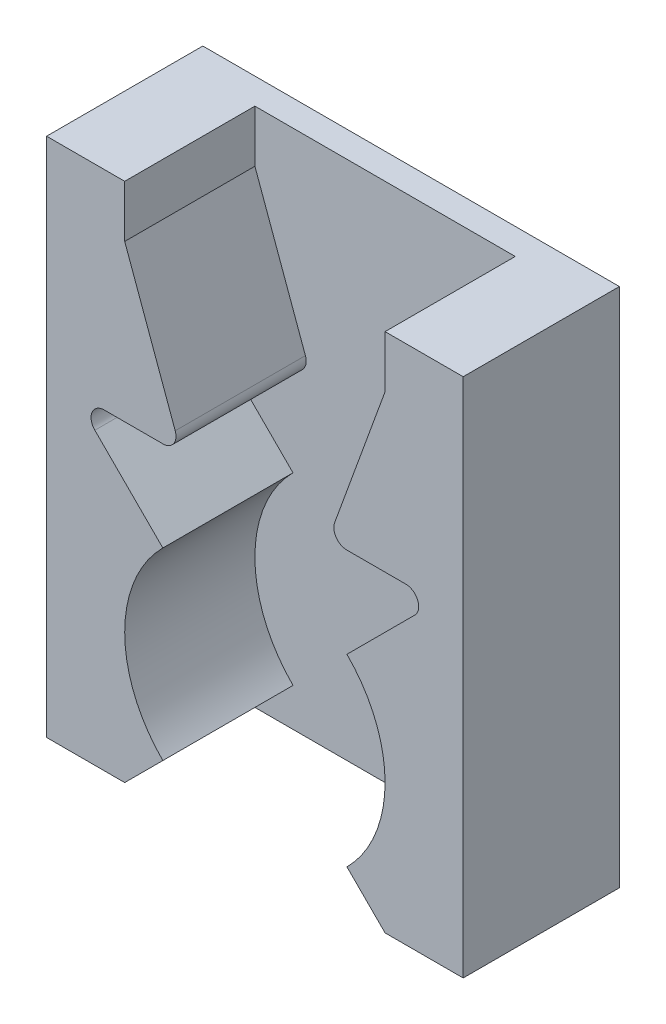
SolidWorks part; units mm, degrees
ref_plane "Front Plane" through (0, 0, 0) normal (0, 0, 1) x (1, 0, 0)
ref_plane "Top Plane" through (0, 0, 0) normal (0, 1, 0) x (1, 0, 0)
ref_plane "Right Plane" through (0, 0, 0) normal (1, 0, 0) x (0, 0, -1)
sketch "Boundaries" plane through (0, 0, 0) normal (0, 0, 1) x (1, 0, 0)
  line L1 (-80, 100) -> (80, 100) construction
  line L2 (-80, 100) -> (-80, -100) construction
  line L3 (-80, -100) -> (80, -100) construction
  line L4 (80, 100) -> (80, -100) construction
  point P0 (0, 0)
  point P6 (0, 0)
  point P7 (0, 100)
  point P8 (80, 0)
  dimension "D1" = 160
  dimension "D2" = 200
sketch "Sketch2" plane through (0, 0, 0) normal (0, 0, 1) x (1, 0, 0)
  line L0 (-80, -100) -> (80, -100) construction
  line L1 (-70, 20) -> (70, 20) construction
  line L2 (-70, 20) -> (-35.3553, -14.6447)
  line L3 (70, 20) -> (35.3553, -14.6447)
  line L4 (-50, 80) -> (50, 80) construction
  line L5 (-50, 80) -> (-28.1618, 20)
  line L6 (50, 80) -> (28.1618, 20)
  line L7 (-70, 20) -> (-28.1618, 20)
  line L8 (-80, 100) -> (-50, 100)
  line L9 (-80, 100) -> (-80, -100)
  line L10 (-80, -100) -> (-50, -100)
  line L11 (80, 100) -> (80, -100)
  line L12 (28.1618, 20) -> (70, 20)
  line L13 (-50, 80) -> (-50, 100)
  line L14 (50, 80) -> (50, 100)
  line L15 (50, 100) -> (80, 100)
  line L16 (-35.3553, -14.6447) -> (50, -100) construction
  line L17 (35.3553, -14.6447) -> (-50, -100) construction
  line L18 (-50, -100) -> (-35.3553, -85.3553)
  line L19 (35.3553, -85.3553) -> (50, -100)
  line L20 (50, -100) -> (80, -100)
  line L21 (-50, -100) -> (50, -100) construction
  arc A0 (-35.3553, -14.6447) -> (-35.3553, -85.3553) centre (0, -50) ccw construction
  arc A1 (-35.3553, -14.6447) -> (-35.3553, -85.3553) centre (0, -50) ccw
  arc A2 (35.3553, -85.3553) -> (35.3553, -14.6447) centre (0, -50) ccw construction
  arc A3 (35.3553, -85.3553) -> (35.3553, -14.6447) centre (0, -50) ccw
  point P12 (0, 20)
  point P13 (0, 80)
  point P26 (0, -100)
  point P27 (-54.4448, 25)
  dimension "D1" = 100
  dimension "D2" = 90
  dimension "D3" = 70
  dimension "D4" = 70
  dimension "D5" = 70
  dimension "D6" = 45
  dimension "D8" = 100
  dimension "D9" = 60
  dimension "D10" = 56.3236
extrude "Boss-Extrude1" add sketch "Sketch2" against normal blind 50
sketch "Sketch3" plane through (0, 0, -50) normal (0, 0, -1) x (-1, 0, 0)
  line L1 (-80, 100) -> (80, 100)
  line L2 (-80, 100) -> (-80, -100)
  line L3 (-80, -100) -> (80, -100)
  line L4 (80, 100) -> (80, -100)
extrude "Boss-Extrude2" add sketch "Sketch3" along normal blind 10 contours L2 L1 L4 L3
fillet "Fillet1" radius 5 4 edges at (-70, 20, -25) (70, 20, -25) (28.1618, 20, -25) (-28.1618, 20, -25)
